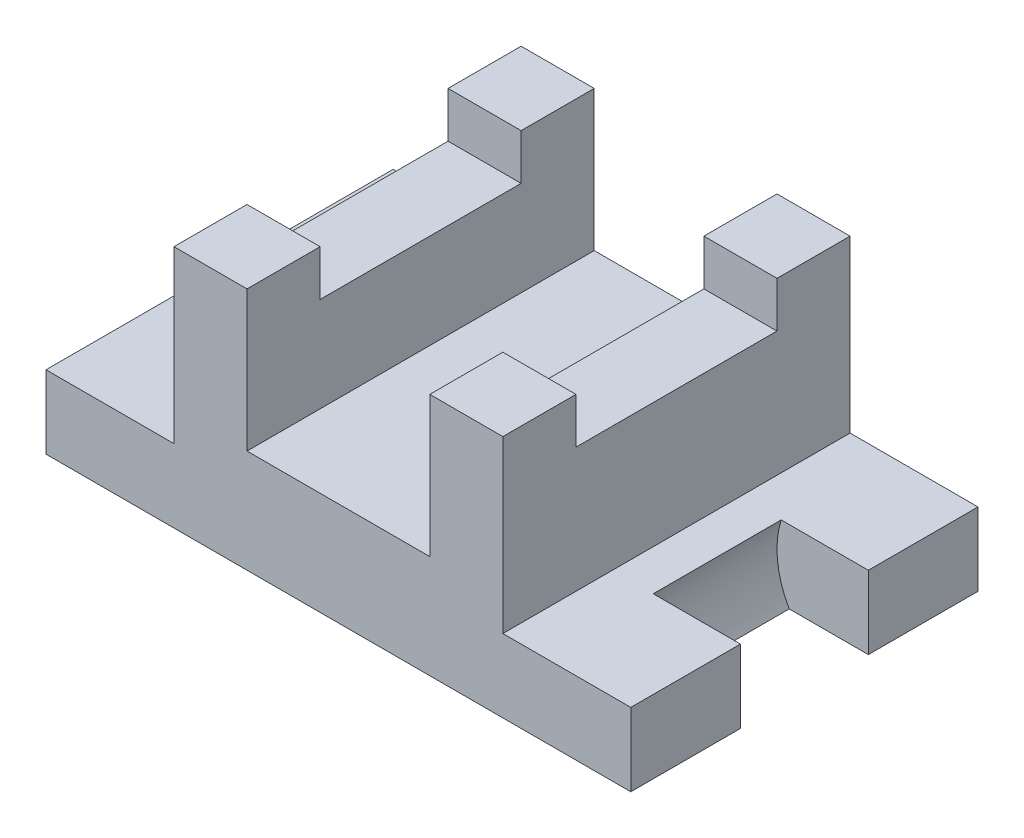
SolidWorks part; units mm, degrees
ref_plane "Front Plane" through (0, 0, 0) normal (0, 0, 1) x (1, 0, 0)
ref_plane "Top Plane" through (0, 0, 0) normal (0, 1, 0) x (1, 0, 0)
ref_plane "Right Plane" through (0, 0, 0) normal (1, 0, 0) x (0, 0, -1)
sketch "Sketch1" plane through (0, 0, 0) normal (0, 0, 1) x (1, 0, 0)
  line L0 (4.0478, 41.0733) -> (-3.9522, 41.0733)
  line L1 (-3.9522, 41.0733) -> (-3.9522, 22.4067)
  line L2 (-3.9522, 22.4067) -> (-17.9522, 22.4067)
  line L3 (-17.9522, 22.4067) -> (-17.9522, 14.4067)
  line L4 (-17.9522, 14.4067) -> (46.0478, 14.4067)
  line L5 (46.0478, 14.4067) -> (46.0478, 22.4067)
  line L6 (46.0478, 22.4067) -> (32.0478, 22.4067)
  line L7 (32.0478, 22.4067) -> (32.0478, 41.0733)
  line L8 (32.0478, 41.0733) -> (24.0478, 41.0733)
  line L9 (24.0478, 41.0733) -> (24.0478, 25.7008)
  line L10 (4.0478, 41.0733) -> (4.0478, 25.7008)
  line L11 (4.0478, 25.7008) -> (24.0478, 25.7008)
  dimension "D1" = 8
  dimension "D2" = 8
  dimension "D3" = 14
  dimension "D4" = 64
  dimension "D5" = 20
extrude "Boss-Extrude1" add sketch "Sketch1" along normal blind 38
sketch "Sketch2" plane through (32.0478, 0, 0) normal (1, 0, 0) x (0, 0, -1)
  line L0 (-38, 41.0733) -> (0, 41.0733) construction
  line L1 (-30, 46.0733) -> (-8, 46.0733)
  line L2 (-30, 46.0733) -> (-30, 36.0733)
  line L3 (-30, 36.0733) -> (-8, 36.0733)
  line L4 (-8, 46.0733) -> (-8, 36.0733)
  line L5 (-30, 46.0733) -> (-8, 36.0733) construction
  line L6 (-30, 36.0733) -> (-8, 46.0733) construction
  line L7 (-38, 22.4067) -> (-38, 41.0733) construction
  line L8 (0, 22.4067) -> (0, 41.0733) construction
  point P0 (-19, 41.0733)
  dimension "D1" = 8
  dimension "D2" = 8
  dimension "D3" = 10
extrude "Cut-Extrude1" cut sketch "Sketch2" against normal through all
sketch "Sketch3" plane through (46.0478, 0, 0) normal (1, 0, 0) x (0, 0, -1)
  line L0 (-38, 14.4067) -> (0, 14.4067) construction
  line L1 (-12, 9.4067) -> (-26, 9.4067)
  line L2 (-12, 9.4067) -> (-12, 19.4067)
  line L3 (-12, 19.4067) -> (-26, 19.4067)
  line L4 (-26, 9.4067) -> (-26, 19.4067)
  line L5 (-12, 9.4067) -> (-26, 19.4067) construction
  line L6 (-12, 19.4067) -> (-26, 9.4067) construction
  line L7 (-38, 14.4067) -> (-38, 22.4067) construction
  line L8 (0, 14.4067) -> (0, 22.4067) construction
  point P0 (-19, 14.4067)
  dimension "D1" = 12
  dimension "D2" = 12
  dimension "D3" = 10
revolve "Cut-Revolve1" cut sketch "Sketch3" angle 360 about L3
